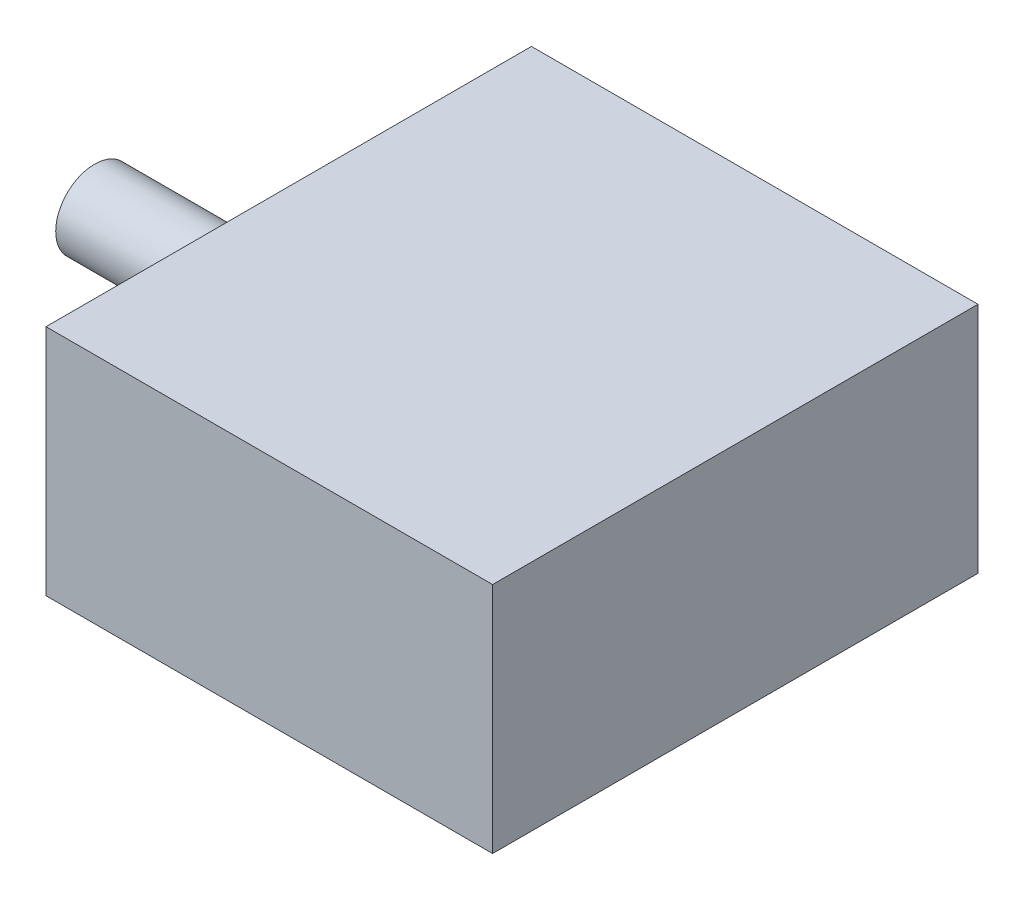
SolidWorks part; units mm, degrees
ref_plane "Plan de face" through (0, 0, 0) normal (0, 0, 1) x (1, 0, 0)
ref_plane "Plan de dessus" through (0, 0, 0) normal (0, 1, 0) x (1, 0, 0)
ref_plane "Plan de droite" through (0, 0, 0) normal (1, 0, 0) x (0, 0, -1)
sketch "Esquisse1" plane through (0, 0, 0) normal (0, 0, 1) x (1, 0, 0)
  line L1 (0, 0) -> (23, 0)
  line L2 (0, 0) -> (0, 12)
  line L3 (0, 12) -> (23, 12)
  line L4 (23, 0) -> (23, 12)
  dimension "D1" = 12
  dimension "D2" = 23
extrude "Boss.-Extru.1" add sketch "Esquisse1" along normal blind 25
sketch "Esquisse2" plane through (0, 0, 0) normal (0, -1, 0) x (-1, 0, 0)
  line L0 (-6.5, 0) -> (-6.5, -25) construction
  line L1 (0, 0) -> (-23, 0) construction
  line L2 (0, -25) -> (-23, -25) construction
  line L3 (-16.5, -25) -> (-16.5, 0) construction
  dimension "D1" = 10
  dimension "D2" = 6.5
sketch "Esquisse4" plane through (0, 0, 0) normal (-1, 0, 0) x (0, 0, 1)
  line L0 (0, 6) -> (25, 6) construction
  line L1 (0, 12) -> (0, 0) construction
  line L2 (25, 12) -> (25, 0) construction
  circle A0 centre (12.5, 6) radius 2
  point P6 (12.5, 6)
extrude "Boss.-Extru.2" add sketch "Esquisse4" along normal blind 10
